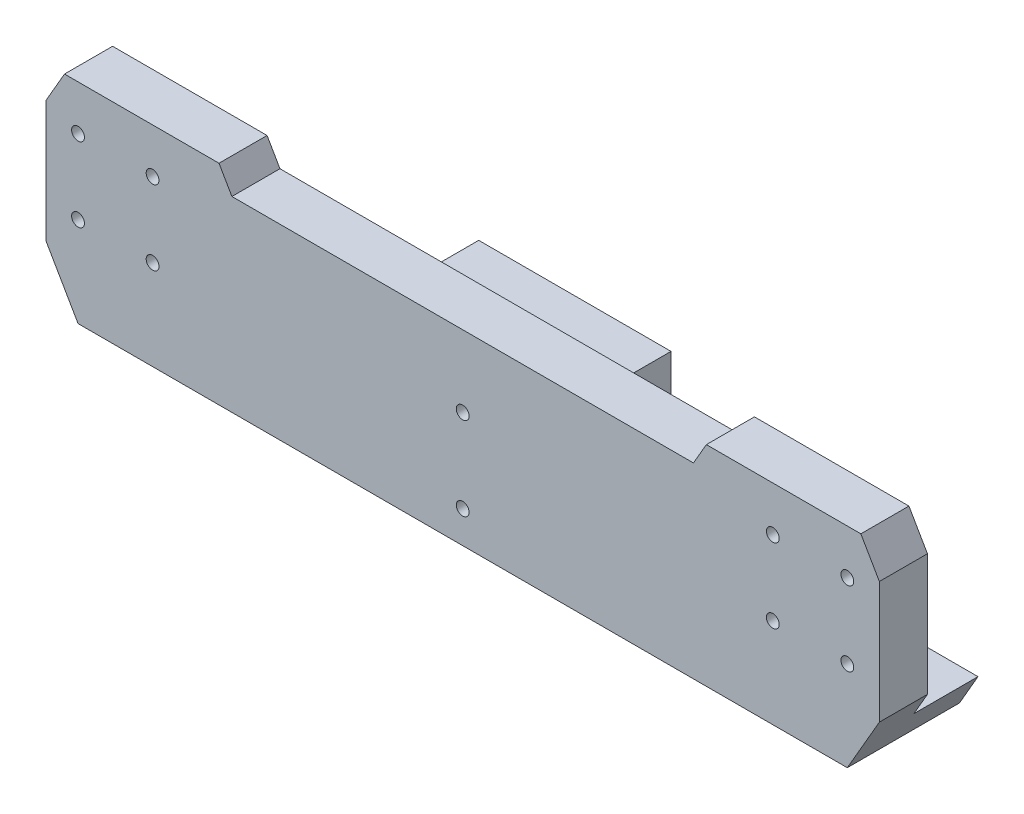
SolidWorks part; units mm, degrees
material "Balsa"
ref_plane "Front Plane" through (0, 0, 0) normal (0, 0, 1) x (1, 0, 0)
ref_plane "Top Plane" through (0, 0, 0) normal (0, 1, 0) x (1, 0, 0)
ref_plane "Right Plane" through (0, 0, 0) normal (1, 0, 0) x (0, 0, -1)
sketch "Sketch1" plane through (0, 0, 0) normal (0, 0, 1) x (1, 0, 0)
  line L0 (130, -41.026) -> (130, -3.026)
  line L1 (130, -3.026) -> (124.2268, 6.9735)
  line L2 (124.2268, 6.9735) -> (76.0261, 6.9735)
  line L3 (76.0261, 6.9735) -> (72, 0)
  line L4 (72, 0) -> (-72, 0)
  line L5 (-72, 0) -> (-76.0261, 6.9735)
  line L6 (-76.0261, 6.9735) -> (-124.2268, 6.9735)
  line L7 (-124.2268, 6.9735) -> (-130, -3.026)
  line L8 (-130, -3.026) -> (-130, -41.026)
  line L9 (-130, -41.026) -> (-120, -58.3465)
  line L10 (-120, -58.3465) -> (120, -58.3465)
  line L11 (120, -58.3465) -> (130, -41.026)
  line L552 (0, -33) -> (0, -7)
  circle A0 centre (-120, -7.0265) radius 2
  circle A1 centre (-96.75, -7.0265) radius 2
  circle A4 centre (-96.75, -30.2765) radius 2
  circle A5 centre (-120, -30.2765) radius 2
  circle A18 centre (120, -7.0265) radius 2
  circle A19 centre (120, -30.2765) radius 2
  circle A21 centre (96.75, -7.0265) radius 2
  circle A23 centre (96.75, -30.2765) radius 2
  circle A24 centre (0, -48.3465) radius 2
  circle A25 centre (0, -22.3465) radius 2
  dimension "D3" = 23.25
  dimension "D4" = 23.25
  dimension "D5" = 14
  dimension "D6" = 10
  dimension "D12" = 26
  dimension "D14" = 130
  dimension "D15" = 4
  dimension "D17" = 4
  dimension "D18" = 36
  dimension "D1" = 65.32
  dimension "D2" = 260
  dimension "D7" = 120
  dimension "D8" = 120
  dimension "D9" = 120
  dimension "D10" = 120
  dimension "D11" = 38
  dimension "D13" = 58
  dimension "D16" = 240
extrude "Boss-Extrude1" add sketch "Sketch1" along normal blind 15
sketch "Sketch2" plane through (0, 0, 15) normal (0, 0, 1) x (1, 0, 0)
  line L8 (-120, -58.3465) -> (120, -58.3465)
  line L9 (-30, -48.3465) -> (30, -48.3465)
  line L10 (-30, -48.3465) -> (-30, -8.3465)
  line L11 (-30, -8.3465) -> (30, -8.3465)
  line L12 (30, -48.3465) -> (30, -8.3465)
  line L13 (120, -58.3465) -> (125.7735, -48.3465)
  line L15 (125.7735, -48.3465) -> (-125.7735, -48.3465)
  line L17 (-125.7735, -48.3465) -> (-120, -58.3465)
  line L18 (120, -58.3465) -> (130, -41.026) construction
  line L19 (-130, -41.026) -> (-120, -58.3465) construction
  line L20 (-130, -3.026) -> (-130, -41.026) construction
  circle A0 centre (0, -22.3465) radius 2
  circle A1 centre (0, -48.3465) radius 2
  dimension "D5" = 4
  dimension "D1" = 10
  dimension "D2" = 40
  dimension "D3" = 60
  dimension "D4" = 100
extrude "Boss-Extrude2" add sketch "Sketch2" against normal blind 35 contours L15 L17 L8 L13 L9 | L9 L12 L11 L10 A1 A0
sketch "Sketch4" plane through (0, -58.3465, 0) normal (0, -1, 0) x (1, 0, 0)
  line L0 (0, 29.5504) -> (0, -51.6603) construction
  line L1 (-120, 15) -> (120, 15) construction
  line L3 (120, 15) -> (120, -20) construction
  circle A0 centre (-72, -2.5) radius 2
  circle A1 centre (-42, -2.5) radius 2
  circle A2 centre (42, -2.5) radius 2
  circle A3 centre (72, -2.5) radius 2
  dimension "D2" = 72
  dimension "D3" = 30
  dimension "D4" = 17.5
  dimension "D5" = 4
  dimension "D1" = 120
extrude "Cut-Extrude1" cut sketch "Sketch4" against normal blind 10
